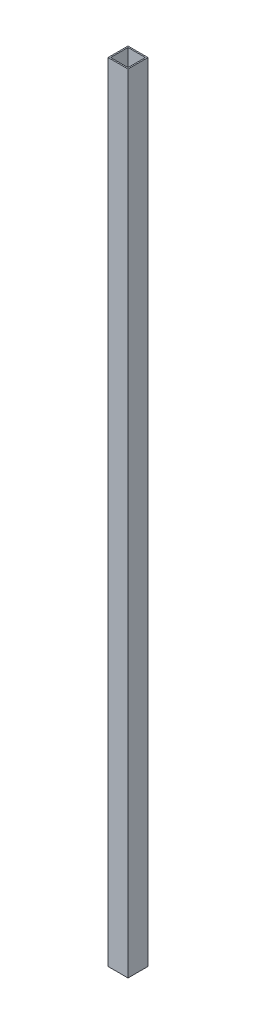
SolidWorks part; units mm, degrees
material "6061 Alloy"
ref_plane "Front Plane" through (0, 0, 0) normal (0, 0, 1) x (1, 0, 0)
ref_plane "Top Plane" through (0, 0, 0) normal (0, 1, 0) x (1, 0, 0)
ref_plane "Right Plane" through (0, 0, 0) normal (1, 0, 0) x (0, 0, -1)
sketch "Sketch1" plane through (0, 0, 0) normal (0, 1, 0) x (1, 0, 0)
  line L1 (-12.7, -12.7) -> (12.7, -12.7)
  line L2 (-12.7, -12.7) -> (-12.7, 12.7)
  line L3 (-12.7, 12.7) -> (12.7, 12.7)
  line L4 (12.7, -12.7) -> (12.7, 12.7)
  line L7 (-11.1125, -11.1125) -> (11.1125, -11.1125)
  line L8 (-11.1125, -11.1125) -> (-11.1125, 11.1125)
  line L9 (-11.1125, 11.1125) -> (11.1125, 11.1125)
  line L10 (11.1125, -11.1125) -> (11.1125, 11.1125)
  point P6 (0, 0)
  dimension "D1" = 25.4
  dimension "D2" = 25.4
  dimension "D3" = 1.5875
  dimension "D4" = 1.5875
  dimension "D5" = 1.5875
extrude "Boss-Extrude1" add sketch "Sketch1" along normal blind 1003.3
